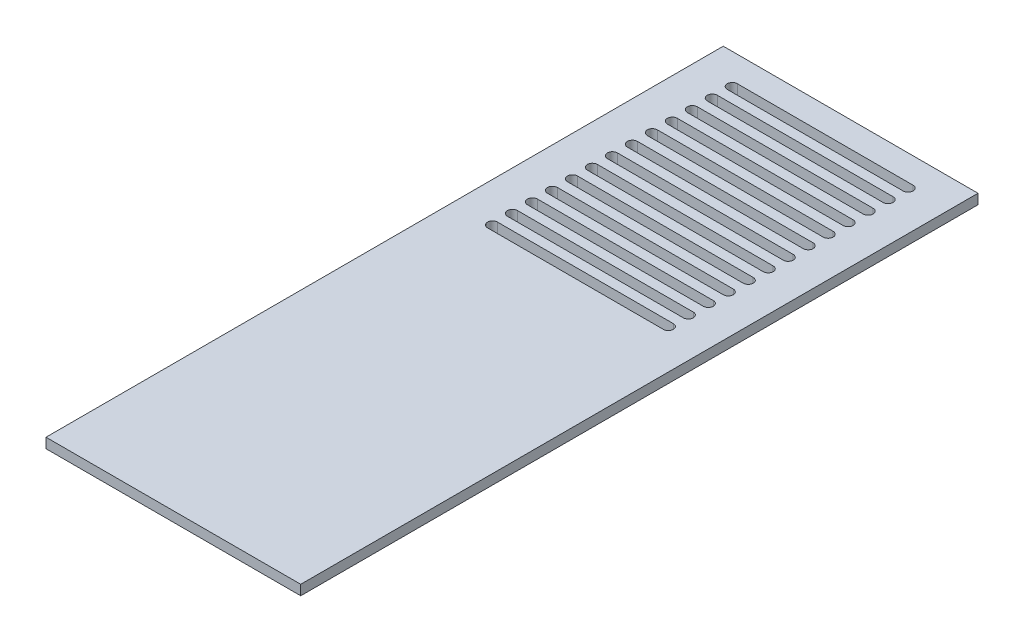
SolidWorks part; units mm, degrees
other "sideDoor"
ref_plane "Front Plane" through (0, 0, 0) normal (0, 0, 1) x (1, 0, 0)
ref_plane "Top Plane" through (0, 0, 0) normal (0, 1, 0) x (1, 0, 0)
ref_plane "Right Plane" through (0, 0, 0) normal (1, 0, 0) x (0, 0, -1)
sketch "Sketch1" plane through (0, 0, 0) normal (0, 1, 0) x (1, 0, 0)
  line L1 (-56, 63.4545) -> (-5, 63.4545)
  line L2 (-56, 63.4545) -> (-56, -72.5455)
  line L3 (-56, -72.5455) -> (-5, -72.5455)
  line L4 (-5, 63.4545) -> (-5, -72.5455)
  dimension "D1" = 136
  dimension "D2" = 51
extrude "Boss-Extrude1" add sketch "Sketch1" along normal blind 2
sketch "Sketch3" plane through (0, 2, 0) normal (0, 1, 0) x (1, 0, 0)
  line L0 (-5, 63.4545) -> (-56, 63.4545) construction
  line L1 (-49.1, 58.3545) -> (-11.9, 58.3545)
  line L2 (-49.1, 58.3545) -> (-49.1, 8.4545)
  line L3 (-49.1, 8.4545) -> (-11.9, 8.4545)
  line L4 (-11.9, 58.3545) -> (-11.9, 8.4545)
  dimension "D1" = 5.1
  dimension "D2" = 37.2
  dimension "D4" = 49.9
sketch "Sketch4" plane through (0, 2, 0) normal (0, 1, 0) x (1, 0, 0)
  line L0 (-48.1, 57.3545) -> (-12.9, 57.3545) construction
  line L1 (-48.1, 58.3545) -> (-12.9, 58.3545)
  line L2 (-48.1, 56.3545) -> (-12.9, 56.3545)
  line L3 (-49.1, 58.3545) -> (-49.1, 8.4545) construction
  line L4 (-49.1, 58.3545) -> (-11.9, 58.3545) construction
  line L5 (-48.1, 53.3545) -> (-12.9, 53.3545) construction
  line L6 (-48.1, 54.3545) -> (-12.9, 54.3545)
  line L7 (-48.1, 52.3545) -> (-12.9, 52.3545)
  line L8 (-48.1, 49.3545) -> (-12.9, 49.3545) construction
  line L9 (-48.1, 50.3545) -> (-12.9, 50.3545)
  line L10 (-48.1, 48.3545) -> (-12.9, 48.3545)
  line L11 (-48.1, 45.3545) -> (-12.9, 45.3545) construction
  line L12 (-48.1, 46.3545) -> (-12.9, 46.3545)
  line L13 (-48.1, 44.3545) -> (-12.9, 44.3545)
  line L14 (-48.1, 41.3545) -> (-12.9, 41.3545) construction
  line L15 (-48.1, 42.3545) -> (-12.9, 42.3545)
  line L16 (-48.1, 40.3545) -> (-12.9, 40.3545)
  line L17 (-48.1, 37.3545) -> (-12.9, 37.3545) construction
  line L18 (-48.1, 38.3545) -> (-12.9, 38.3545)
  line L19 (-48.1, 36.3545) -> (-12.9, 36.3545)
  line L20 (-48.1, 33.3545) -> (-12.9, 33.3545) construction
  line L21 (-48.1, 34.3545) -> (-12.9, 34.3545)
  line L22 (-48.1, 32.3545) -> (-12.9, 32.3545)
  line L23 (-48.1, 29.3545) -> (-12.9, 29.3545) construction
  line L24 (-48.1, 30.3545) -> (-12.9, 30.3545)
  line L25 (-48.1, 28.3545) -> (-12.9, 28.3545)
  line L26 (-48.1, 25.3545) -> (-12.9, 25.3545) construction
  line L27 (-48.1, 26.3545) -> (-12.9, 26.3545)
  line L28 (-48.1, 24.3545) -> (-12.9, 24.3545)
  line L29 (-48.1, 21.3545) -> (-12.9, 21.3545) construction
  line L30 (-48.1, 22.3545) -> (-12.9, 22.3545)
  line L31 (-48.1, 20.3545) -> (-12.9, 20.3545)
  line L32 (-48.1, 17.3545) -> (-12.9, 17.3545) construction
  line L33 (-48.1, 18.3545) -> (-12.9, 18.3545)
  line L34 (-48.1, 16.3545) -> (-12.9, 16.3545)
  line L35 (-48.1, 13.3545) -> (-12.9, 13.3545) construction
  line L36 (-48.1, 14.3545) -> (-12.9, 14.3545)
  line L37 (-48.1, 12.3545) -> (-12.9, 12.3545)
  line L38 (-48.1, 9.3545) -> (-12.9, 9.3545) construction
  line L39 (-48.1, 10.3545) -> (-12.9, 10.3545)
  line L40 (-48.1, 8.3545) -> (-12.9, 8.3545)
  arc A0 (-48.1, 58.3545) -> (-48.1, 56.3545) centre (-48.1, 57.3545) ccw
  arc A1 (-12.9, 56.3545) -> (-12.9, 58.3545) centre (-12.9, 57.3545) ccw
  arc A2 (-48.1, 54.3545) -> (-48.1, 52.3545) centre (-48.1, 53.3545) ccw
  arc A3 (-12.9, 52.3545) -> (-12.9, 54.3545) centre (-12.9, 53.3545) ccw
  arc A4 (-48.1, 50.3545) -> (-48.1, 48.3545) centre (-48.1, 49.3545) ccw
  arc A5 (-12.9, 48.3545) -> (-12.9, 50.3545) centre (-12.9, 49.3545) ccw
  arc A6 (-48.1, 46.3545) -> (-48.1, 44.3545) centre (-48.1, 45.3545) ccw
  arc A7 (-12.9, 44.3545) -> (-12.9, 46.3545) centre (-12.9, 45.3545) ccw
  arc A8 (-48.1, 42.3545) -> (-48.1, 40.3545) centre (-48.1, 41.3545) ccw
  arc A9 (-12.9, 40.3545) -> (-12.9, 42.3545) centre (-12.9, 41.3545) ccw
  arc A10 (-48.1, 38.3545) -> (-48.1, 36.3545) centre (-48.1, 37.3545) ccw
  arc A11 (-12.9, 36.3545) -> (-12.9, 38.3545) centre (-12.9, 37.3545) ccw
  arc A12 (-48.1, 34.3545) -> (-48.1, 32.3545) centre (-48.1, 33.3545) ccw
  arc A13 (-12.9, 32.3545) -> (-12.9, 34.3545) centre (-12.9, 33.3545) ccw
  arc A14 (-48.1, 30.3545) -> (-48.1, 28.3545) centre (-48.1, 29.3545) ccw
  arc A15 (-12.9, 28.3545) -> (-12.9, 30.3545) centre (-12.9, 29.3545) ccw
  arc A16 (-48.1, 26.3545) -> (-48.1, 24.3545) centre (-48.1, 25.3545) ccw
  arc A17 (-12.9, 24.3545) -> (-12.9, 26.3545) centre (-12.9, 25.3545) ccw
  arc A18 (-48.1, 22.3545) -> (-48.1, 20.3545) centre (-48.1, 21.3545) ccw
  arc A19 (-12.9, 20.3545) -> (-12.9, 22.3545) centre (-12.9, 21.3545) ccw
  arc A20 (-48.1, 18.3545) -> (-48.1, 16.3545) centre (-48.1, 17.3545) ccw
  arc A21 (-12.9, 16.3545) -> (-12.9, 18.3545) centre (-12.9, 17.3545) ccw
  arc A22 (-48.1, 14.3545) -> (-48.1, 12.3545) centre (-48.1, 13.3545) ccw
  arc A23 (-12.9, 12.3545) -> (-12.9, 14.3545) centre (-12.9, 13.3545) ccw
  arc A24 (-48.1, 10.3545) -> (-48.1, 8.3545) centre (-48.1, 9.3545) ccw
  arc A25 (-12.9, 8.3545) -> (-12.9, 10.3545) centre (-12.9, 9.3545) ccw
  point P2 (-30.5, 57.3545)
  point P7 (-49.1, 57.3545)
  point P16 (-30.5, 53.3545)
  point P23 (-30.5, 49.3545)
  point P30 (-30.5, 45.3545)
  point P37 (-30.5, 41.3545)
  point P44 (-30.5, 37.3545)
  point P51 (-30.5, 33.3545)
  point P58 (-30.5, 29.3545)
  point P65 (-30.5, 25.3545)
  point P72 (-30.5, 21.3545)
  point P79 (-30.5, 17.3545)
  point P86 (-30.5, 13.3545)
  point P93 (-30.5, 9.3545)
  dimension "D1" = 0
  dimension "D3" = 13
  dimension "D2" = 0
extrude "Cut-Extrude1" cut sketch "Sketch4" against normal blind 10
sketch "Sketch5" plane through (0, 0, -63.4545) normal (0, 0, -1) x (-1, 0, 0)
  line L1 (56, 2) -> (57, 2)
  line L2 (56, 2) -> (56, 0)
  line L3 (56, 0) -> (57, 0)
  line L4 (57, 2) -> (57, 0)
  line L5 (5, 2) -> (4, 2)
  line L6 (5, 2) -> (5, 0)
  line L7 (5, 0) -> (4, 0)
  line L8 (4, 2) -> (4, 0)
  point P10 (57, 1)
  dimension "D1" = 1
  dimension "D2" = 1
extrude "Boss-Extrude2" add sketch "Sketch5" against normal up to surface (136 mm away) up to face at (-30.5, 1, 72.5455)
sketch "Sketch6" plane through (0, 0, -63.4545) normal (0, 0, -1) x (-1, 0, 0)
  line L1 (57, 0) -> (58, 0)
  line L2 (57, 0) -> (57, 2)
  line L3 (57, 2) -> (58, 2)
  line L4 (58, 0) -> (58, 2)
  line L5 (4, 0) -> (3, 0)
  line L6 (4, 0) -> (4, 2)
  line L7 (4, 2) -> (3, 2)
  line L8 (3, 0) -> (3, 2)
  dimension "D1" = 1
  dimension "D2" = 1
extrude "Boss-Extrude3" add sketch "Sketch6" against normal up to surface (136 mm away) up to face at (-30.5, 1, 72.5455)
sketch "Sketch7" plane through (0, 0, 72.5455) normal (0, 0, 1) x (1, 0, 0)
  line L1 (-66.7377, 9.812) -> (2.0582, 9.812)
  line L2 (-66.7377, 9.812) -> (-66.7377, -16.6136)
  line L3 (-66.7377, -16.6136) -> (2.0582, -16.6136)
  line L4 (2.0582, 9.812) -> (2.0582, -16.6136)
extrude "Cut-Extrude2" cut sketch "Sketch7" against normal blind 0.4
sketch "Sketch8" plane through (0, 0, -63.4545) normal (0, 0, -1) x (-1, 0, 0)
  line L0 (3, 0) -> (58, 0) construction
  line L1 (3, 2) -> (5, 2)
  line L2 (3, 2) -> (3, 0)
  line L3 (3, 0) -> (5, 0)
  line L4 (5, 2) -> (5, 0)
  line L6 (58, 2) -> (56, 2)
  line L7 (58, 2) -> (58, 0)
  line L8 (58, 0) -> (56, 0)
  line L9 (56, 2) -> (56, 0)
  dimension "D1" = 2
  dimension "D2" = 2
extrude "Cut-Extrude3" cut sketch "Sketch8" against normal blind 135.6
